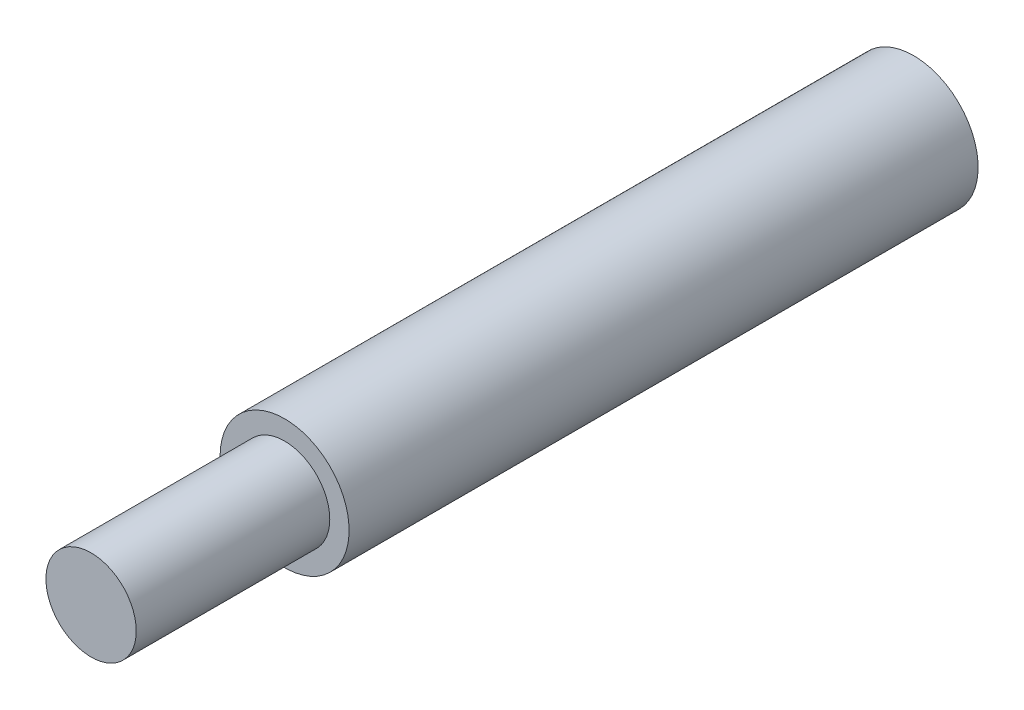
SolidWorks part; units mm, degrees
ref_plane "Front Plane" through (0, 0, 0) normal (0, 0, 1) x (1, 0, 0)
ref_plane "Top Plane" through (0, 0, 0) normal (0, 1, 0) x (1, 0, 0)
ref_plane "Right Plane" through (0, 0, 0) normal (1, 0, 0) x (0, 0, -1)
sketch "Sketch1" plane through (0, 0, 0) normal (0, 0, 1) x (1, 0, 0)
  circle A0 centre (0, 0) radius 1.4
  dimension "D1" = 2.8
extrude "Boss-Extrude1" add sketch "Sketch1" along normal blind 6
sketch "Sketch2" plane through (0, 0, 0) normal (0, 0, -1) x (-1, 0, 0)
  circle A0 centre (0, 0) radius 2
  dimension "D1" = 4
extrude "Boss-Extrude2" add sketch "Sketch2" along normal blind 19.5
sketch "Sketch3" plane through (0, 0, -19.5) normal (0, 0, -1) x (-1, 0, 0)
  circle A0 centre (0, 0) radius 1.4
  dimension "D1" = 2.8
extrude "Cut-Extrude1" cut sketch "Sketch3" against normal blind 10
